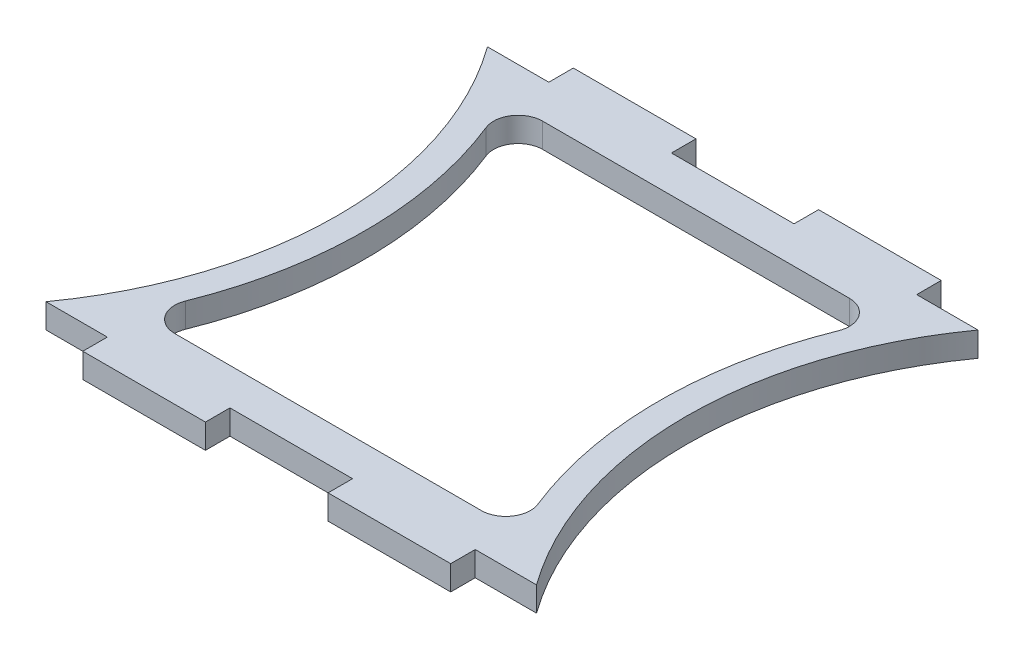
SolidWorks part; units mm, degrees
ref_plane "Front Plane" through (0, 0, 0) normal (0, 0, 1) x (1, 0, 0)
ref_plane "Top Plane" through (0, 0, 0) normal (0, 1, 0) x (1, 0, 0)
ref_plane "Right Plane" through (0, 0, 0) normal (1, 0, 0) x (0, 0, -1)
sketch "Sketch1" plane through (0, 0, 0) normal (0, 1, 0) x (1, 0, 0)
  line L0 (0, 0) -> (225.8585, 0) construction
  line L1 (-20, -18) -> (-15, -18)
  line L2 (-12.5038, 15) -> (12.5038, 15)
  line L3 (-20, 18) -> (-15, 18)
  line L4 (-12.5038, -15) -> (12.5038, -15)
  line L5 (-20, -18) -> (20, 18) construction
  line L6 (-20, 18) -> (20, -18) construction
  line L7 (0, -30) -> (0, 30) construction
  line L8 (-15, 18) -> (-15, 20)
  line L9 (-15, 20) -> (-5, 20)
  line L10 (-5, 20) -> (-5, 18)
  line L11 (5, 20) -> (5, 18)
  line L12 (15, 20) -> (5, 20)
  line L13 (15, 18) -> (15, 20)
  line L14 (-5, 18) -> (5, 18)
  line L15 (15, 18) -> (20, 18)
  line L16 (15, -18) -> (15, -20)
  line L17 (15, -20) -> (5, -20)
  line L18 (5, -20) -> (5, -18)
  line L19 (-5, -20) -> (-5, -18)
  line L20 (-15, -20) -> (-5, -20)
  line L21 (-15, -18) -> (-15, -20)
  line L22 (-5, -18) -> (5, -18)
  line L23 (15, -18) -> (20, -18)
  arc A0 (20, 18) -> (20, -18) centre (45, 0) ccw
  arc A1 (-20, 18) -> (-20, -18) centre (-45, 0) cw
  arc A2 (14.3608, 12.2571) -> (14.3608, -12.2571) centre (45, 0) ccw
  arc A3 (-14.3608, 12.2571) -> (-14.3608, -12.2571) centre (-45, 0) cw
  arc A4 (-12.5038, -15) -> (-14.3608, -12.2571) centre (-12.5038, -13) cw
  arc A5 (14.3608, -12.2571) -> (12.5038, -15) centre (12.5038, -13) cw
  arc A6 (12.5038, 15) -> (14.3608, 12.2571) centre (12.5038, 13) cw
  arc A7 (-14.3608, 12.2571) -> (-12.5038, 15) centre (-12.5038, 13) cw
  point P0 (0, 0)
  dimension "D4" = 66
  dimension "D5" = 2
  dimension "D1" = 40
  dimension "D2" = 36
  dimension "D3" = 45
extrude "Boss-Extrude1" add sketch "Sketch1" along normal blind 2
